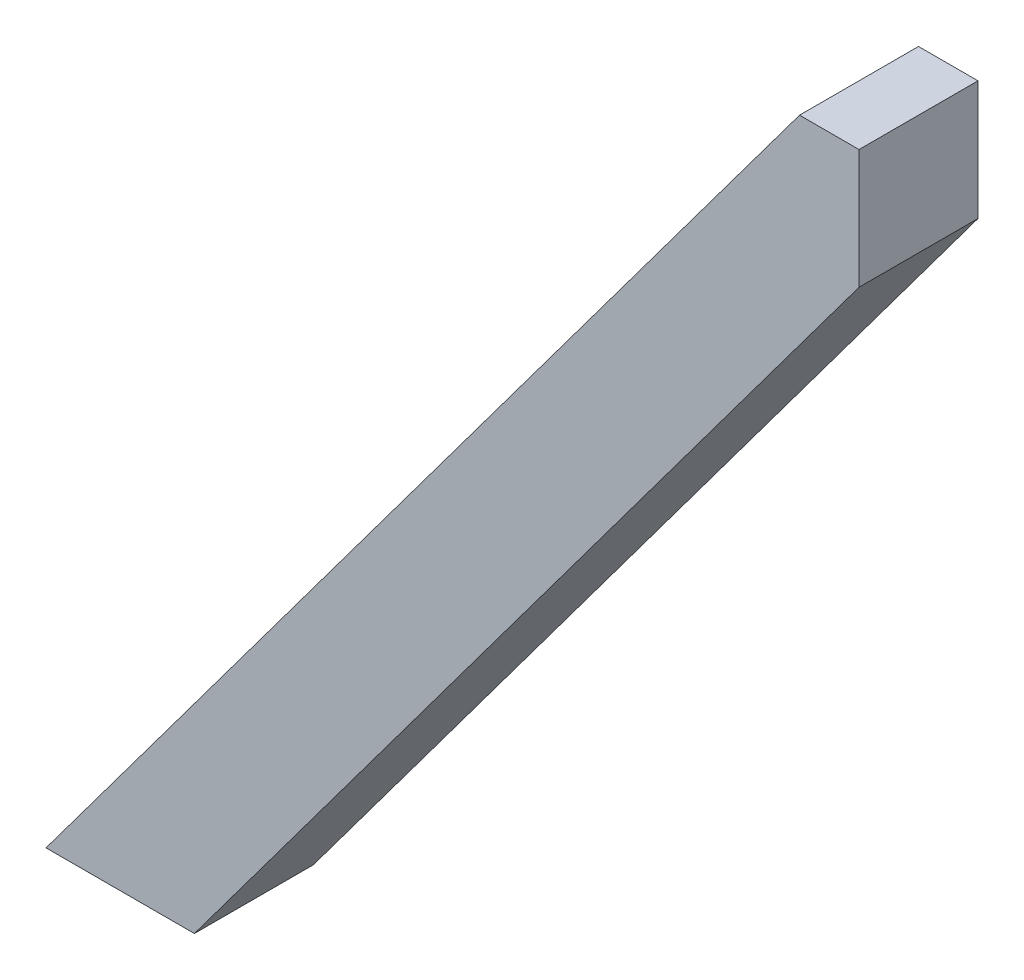
SolidWorks part; units mm, degrees
material "6061-T6 (SS)"
ref_plane "Front" through (0, 0, 0) normal (0, 0, 1) x (1, 0, 0)
ref_plane "Top" through (0, 0, 0) normal (0, 1, 0) x (1, 0, 0)
ref_plane "Right" through (0, 0, 0) normal (1, 0, 0) x (0, 0, -1)
sketch "Sketch1" plane through (0, 0, 0) normal (0, 0, 1) x (1, 0, 0)
  line L0 (0, 0) -> (95.0267, 0)
  line L1 (95.0267, 0) -> (520.7031, 571.2968)
  line L2 (520.7031, 571.2968) -> (520.7031, 647.6977)
  line L3 (520.7031, 647.6977) -> (482.6031, 647.6977)
  line L4 (482.6031, 647.6977) -> (0, 0)
  dimension "D1" = 76.2
  dimension "D2" = 53.31
  dimension "D3" = 807.724
  dimension "D4" = 38.1
extrude "Boss-Extrude1" add sketch "Sketch1" along normal blind 76.2
